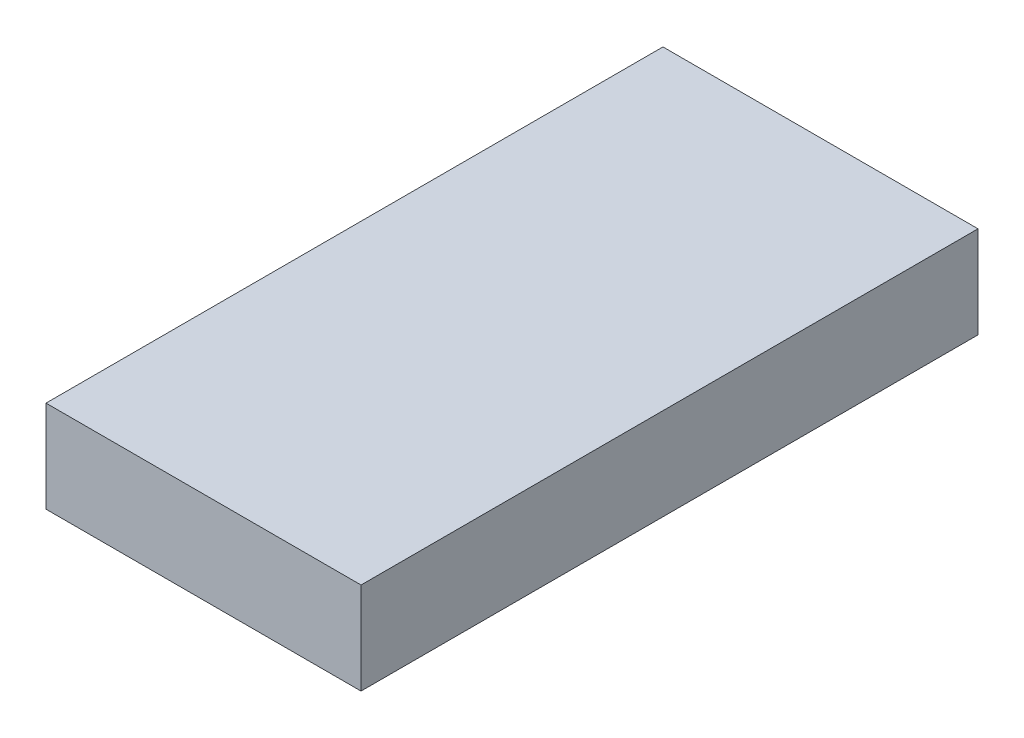
SolidWorks part; units mm, degrees
ref_plane "Front" through (0, 0, 0) normal (0, 0, 1) x (1, 0, 0)
ref_plane "Top" through (0, 0, 0) normal (0, 1, 0) x (1, 0, 0)
ref_plane "Right" through (0, 0, 0) normal (1, 0, 0) x (0, 0, -1)
sketch "Sketch1" plane through (0, 0, 0) normal (0, 0, 1) x (1, 0, 0)
  line L1 (-60.96, 17.78) -> (60.96, 17.78)
  line L2 (-60.96, 17.78) -> (-60.96, -17.78)
  line L3 (-60.96, -17.78) -> (60.96, -17.78)
  line L4 (60.96, 17.78) -> (60.96, -17.78)
  line L5 (-60.96, 17.78) -> (60.96, -17.78) construction
  line L6 (-60.96, -17.78) -> (60.96, 17.78) construction
  point P0 (0, 0)
  dimension "D1" = 121.92
  dimension "D2" = 35.56
extrude "Boss-Extrude1" add sketch "Sketch1" along normal blind 238.76
